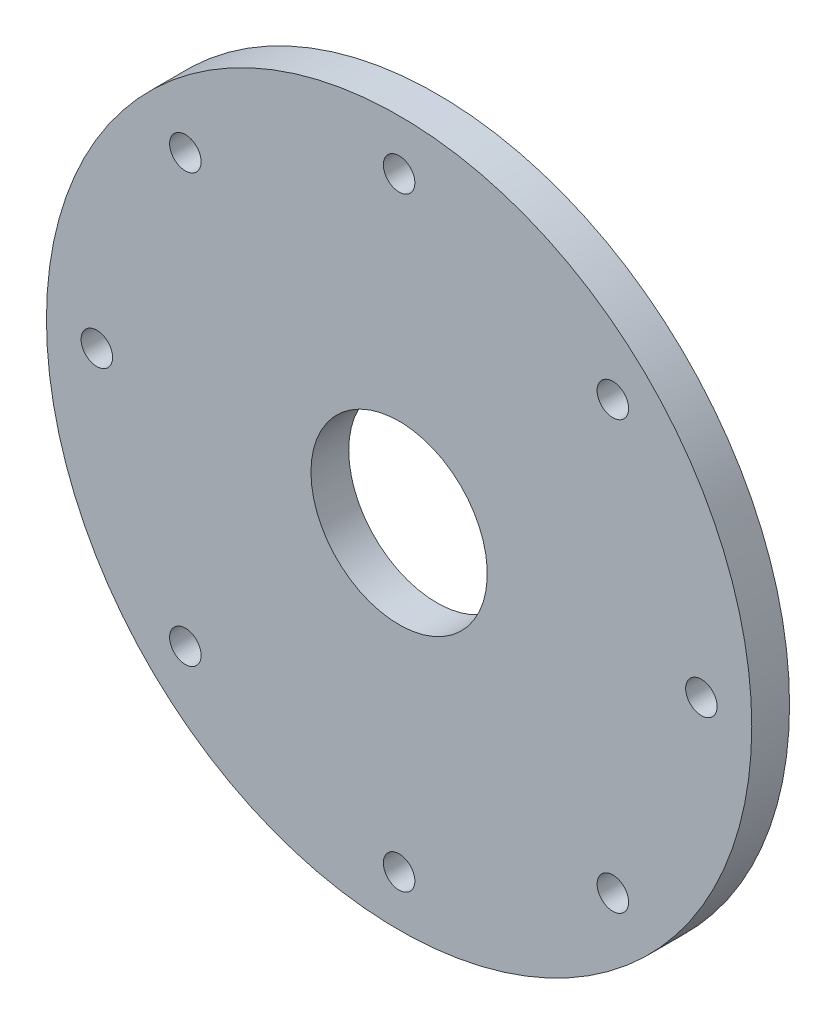
SolidWorks part; units mm, degrees
ref_plane "Front Plane" through (0, 0, 0) normal (0, 0, 1) x (1, 0, 0)
ref_plane "Top Plane" through (0, 0, 0) normal (0, 1, 0) x (1, 0, 0)
ref_plane "Right Plane" through (0, 0, 0) normal (1, 0, 0) x (0, 0, -1)
sketch "Sketch1" plane through (0, 0, 0) normal (0, 0, 1) x (1, 0, 0)
  circle A0 centre (0, 0) radius 22.225
  circle A1 centre (0, 0) radius 19.05 construction
  circle A2 centre (-19.05, 0) radius 0.9922
  circle A3 centre (-13.4704, 13.4704) radius 0.9922
  circle A4 centre (0, 19.05) radius 0.9922
  circle A5 centre (13.4704, 13.4704) radius 0.9922
  circle A6 centre (19.05, 0) radius 0.9922
  circle A7 centre (13.4704, -13.4704) radius 0.9922
  circle A8 centre (0, -19.05) radius 0.9922
  circle A9 centre (-13.4704, -13.4704) radius 0.9922
  circle A10 centre (0, 0) radius 5.5562
  point P22 (0, 0)
  dimension "D1" = 44.45
  dimension "D2" = 38.1
  dimension "D3" = 1.9844
  dimension "D4" = 8
extrude "Boss-Extrude1" add sketch "Sketch1" along normal blind 2.3813
